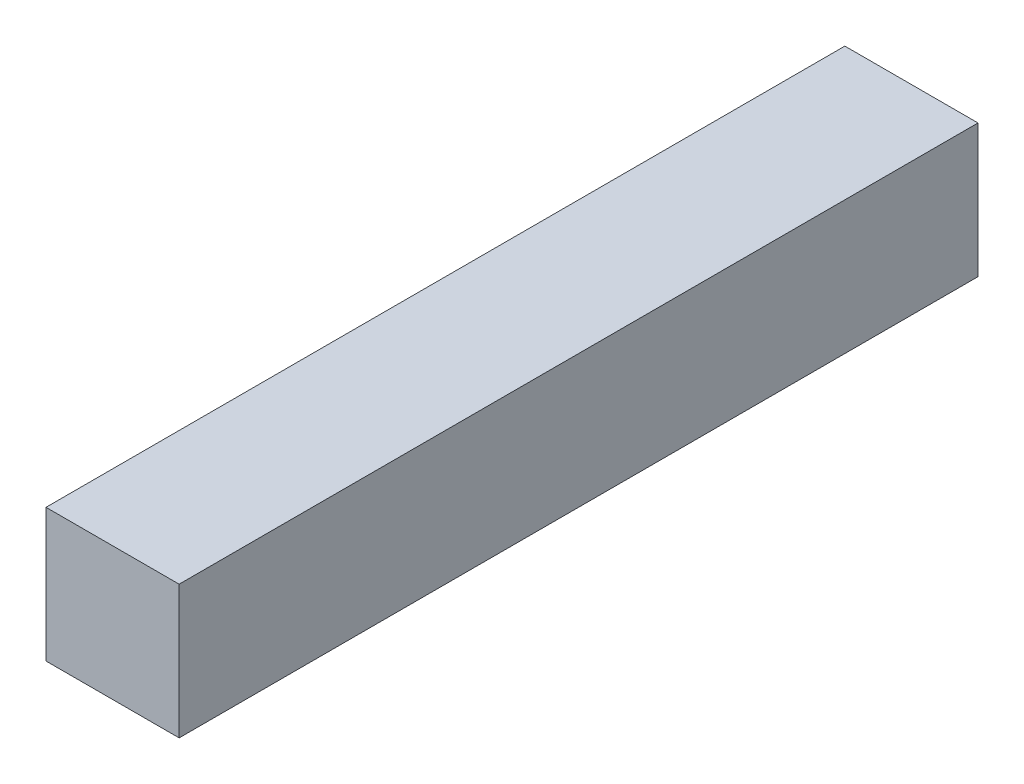
SolidWorks part; units mm, degrees
ref_plane "Front Plane" through (0, 0, 0) normal (0, 0, 1) x (1, 0, 0)
ref_plane "Top Plane" through (0, 0, 0) normal (0, 1, 0) x (1, 0, 0)
ref_plane "Right Plane" through (0, 0, 0) normal (1, 0, 0) x (0, 0, -1)
sketch "Sketch1" plane through (0, 0, 0) normal (0, 0, 1) x (1, 0, 0)
  line L1 (-12.7, -12.7) -> (12.7, -12.7)
  line L2 (-12.7, -12.7) -> (-12.7, 12.7)
  line L3 (-12.7, 12.7) -> (12.7, 12.7)
  line L4 (12.7, -12.7) -> (12.7, 12.7)
  line L5 (-12.7, -12.7) -> (12.7, 12.7) construction
  line L6 (-12.7, 12.7) -> (12.7, -12.7) construction
  point P0 (0, 0)
  dimension "D1" = 25.4
extrude "Boss-Extrude1" add sketch "Sketch1" along normal mid plane 152.4
